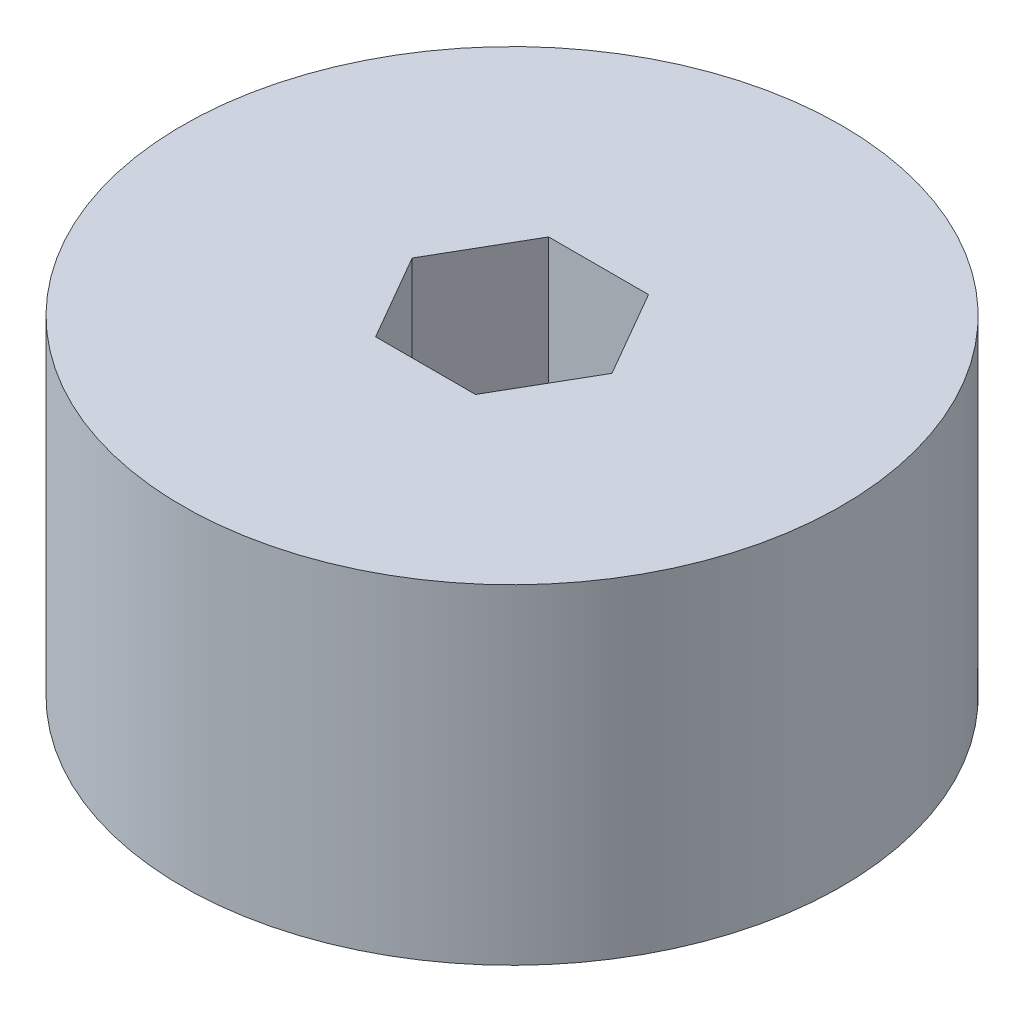
SolidWorks part; units mm, degrees
material "Custom Plastic"
ref_plane "Front Plane" through (0, 0, 0) normal (0, 0, 1) x (1, 0, 0)
ref_plane "Top Plane" through (0, 0, 0) normal (0, 1, 0) x (1, 0, 0)
ref_plane "Right Plane" through (0, 0, 0) normal (1, 0, 0) x (0, 0, -1)
sketch "Sketch1" plane through (0, 0, 0) normal (0, 1, 0) x (1, 0, 0)
  circle A0 centre (0, 0) radius 4.7625
  dimension "D1" = 9.525
extrude "Boss-Extrude1" add sketch "Sketch1" along normal blind 4.7625
sketch "Sketch2" plane through (0, 0, 0) normal (0, -1, 0) x (1, 0, 0)
  line L1 (0.7217, 1.25) -> (-0.7217, 1.25)
  line L2 (-0.7217, 1.25) -> (-1.4434, 0)
  line L3 (-1.4434, 0) -> (-0.7217, -1.25)
  line L4 (-0.7217, -1.25) -> (0.7217, -1.25)
  line L5 (0.7217, -1.25) -> (1.4434, 0)
  line L6 (1.4434, 0) -> (0.7217, 1.25)
  circle A0 centre (0, 0) radius 1.25 construction
  dimension "D1" = 2.5
extrude "Cut-Extrude1" cut sketch "Sketch2" against normal through all
